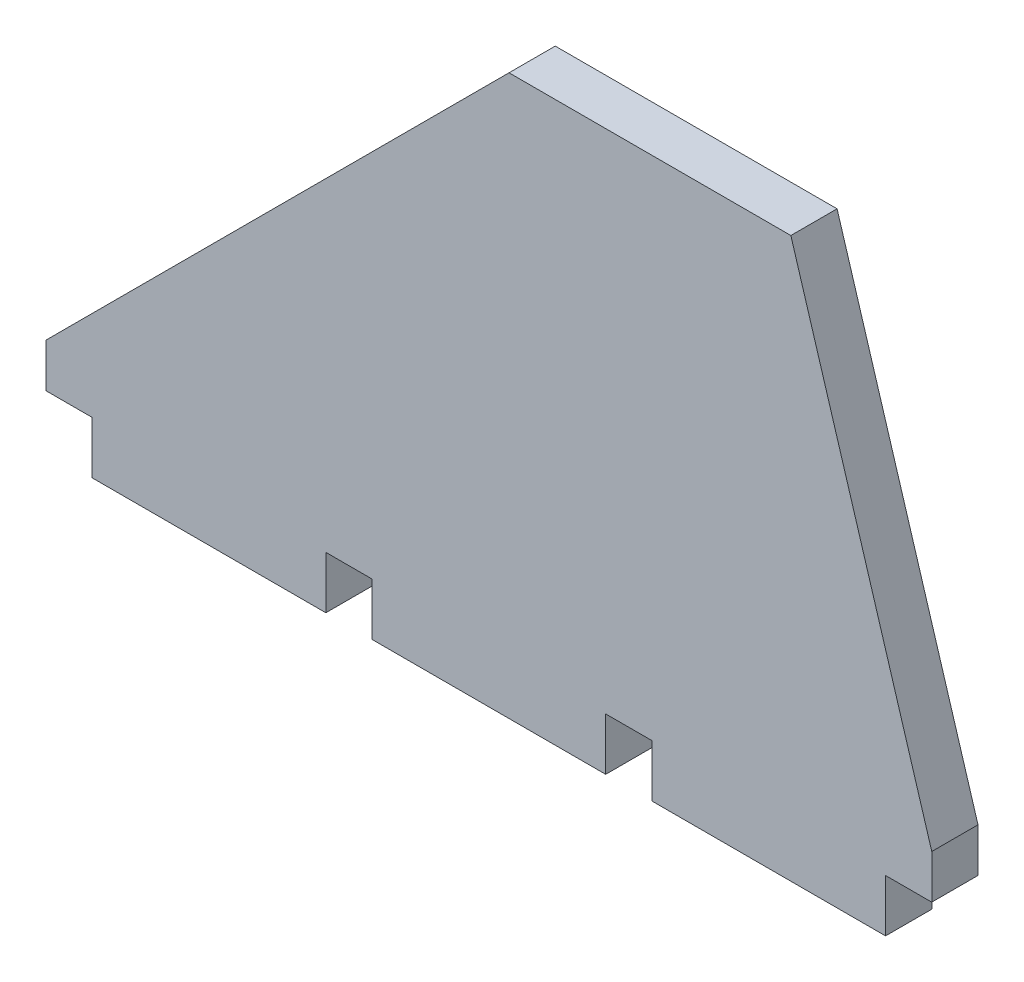
SolidWorks part; units mm, degrees
material "Zoltek Panex 33"
ref_plane "Ebene vorne" through (0, 0, 0) normal (0, 0, 1) x (1, 0, 0)
ref_plane "Ebene oben" through (0, 0, 0) normal (0, 1, 0) x (1, 0, 0)
ref_plane "Ebene rechts" through (0, 0, 0) normal (1, 0, 0) x (0, 0, -1)
sketch "Sketch1" plane through (0, 0, 0) normal (0, 0, 1) x (1, 0, 0)
  line L0 (0, 0) -> (11.482, 0)
  line L1 (11.482, 0) -> (11.482, -13)
  line L2 (11.482, -13) -> (69.506, -13)
  line L3 (69.506, -13) -> (69.506, 0)
  line L4 (69.506, 0) -> (80.988, 0)
  line L5 (80.988, 0) -> (80.988, -13)
  line L6 (80.988, -13) -> (139.012, -13)
  line L7 (139.012, -13) -> (139.012, 0)
  line L8 (139.012, 0) -> (150.494, 0)
  line L9 (150.494, 0) -> (150.494, -13)
  line L10 (150.494, -13) -> (208.518, -13)
  line L11 (208.518, -13) -> (208.518, 0)
  line L12 (208.518, 0) -> (220, 0)
  line L13 (220, 0) -> (220, 10.9)
  line L14 (220, 10.9) -> (185, 125.9)
  line L15 (185, 125.9) -> (115, 125.9)
  line L16 (115, 125.9) -> (0, 10.9)
  line L17 (0, 10.9) -> (0, 0)
  line L18 (11.482, 0) -> (69.506, 0) construction
  line L19 (80.988, 0) -> (139.012, 0) construction
  line L20 (150.494, 0) -> (208.518, 0) construction
  line L21 (0, 10.9) -> (220, 10.9) construction
  dimension "D1" = 220
  dimension "D2" = 11.482
  dimension "D3" = 11.482
  dimension "D4" = 11.482
  dimension "D5" = 11.482
  dimension "D6" = 13
  dimension "D7" = 23.9
  dimension "D8" = 45
  dimension "D9" = 115
  dimension "D10" = 70
extrude "Boss-Extrude1" add sketch "Sketch1" along normal blind 11.482
equation "\"d_i_tube\"= 150mm'Inner Rocket Body Composite Tube Diameter"
equation "\"t_tube\"= 1.182mm'Thickness of Rocket Body Composite Tube"
equation "\"l_upper_body_tube\"= 949.3mm'Upper Rocket Body Composite Tube length"
equation "\"l_lower_body_tube\"= 816mm'Lower Rocket Body Composite Tube Length"
equation "\"d_a_NC\"= 154mm'Outer Diameter of Nosecone base"
equation "\"d_i_phenolic_tube\"= 152.3mm'Inner Phenolic Tube Diameter"
equation "\"t_phenolic_tube\"= 2mm'Thickness of Phenolic Body Tube"
equation "\"l_fin_cut\"= 220mm'Length of fin on Motor Retainer"
equation "\"t_SW-Panel\"= 11.482mm'Thickness of Sandwich-Panel"
equation "\"l_motor_tube\"=610mm'Length of phenolic motor tube"
equation "\"d_i_motor_tube\"=99.06mm'Inner diameter of phenolic motor tube"
equation "\"t_motor_tube\"=1.58mm'Thicknes of phenolic motor tube"
equation "\"l_cut_fin_centering\"=13mm'Length of cut for fin alignement on fin centering rings"
equation "\"l_M3_threaded_rods\"=220mm'Length of M3 threaded rods for thrust plate force transmission"
equation "\"D2@Sketch1\"=\"t_SW-Panel\""
equation "\"D3@Sketch1\"=\"t_SW-Panel\""
equation "\"D4@Sketch1\"=\"t_SW-Panel\""
equation "\"D5@Sketch1\"=\"t_SW-Panel\""
equation "\"D6@Sketch1\"=\"l_cut_fin_centering\""
equation "\"D7@Sketch1\"=(\"d_i_tube\"-102.2)/2"
equation "\"D1@Boss-Extrude1\"=\"t_SW-Panel\""
